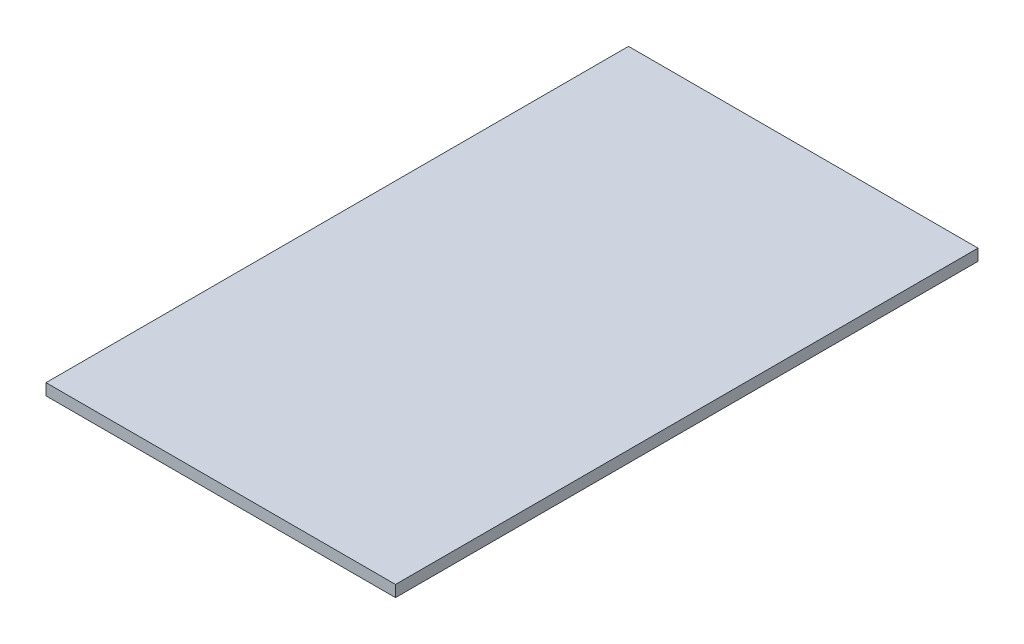
SolidWorks part; units mm, degrees
ref_plane "Front Plane" through (0, 0, 0) normal (0, 0, 1) x (1, 0, 0)
ref_plane "Top Plane" through (0, 0, 0) normal (0, 1, 0) x (1, 0, 0)
ref_plane "Right Plane" through (0, 0, 0) normal (1, 0, 0) x (0, 0, -1)
sketch "Sketch1" plane through (0, 0, 0) normal (0, 1, 0) x (1, 0, 0)
  line L1 (15.24, -25.4) -> (-15.24, -25.4)
  line L2 (15.24, -25.4) -> (15.24, 25.4)
  line L3 (15.24, 25.4) -> (-15.24, 25.4)
  line L4 (-15.24, -25.4) -> (-15.24, 25.4)
  line L5 (15.24, -25.4) -> (-15.24, 25.4) construction
  line L6 (15.24, 25.4) -> (-15.24, -25.4) construction
  point P0 (0, 0)
  dimension "D1" = 30.48
  dimension "D2" = 50.8
extrude "Boss-Extrude1" add sketch "Sketch1" along normal blind 1
